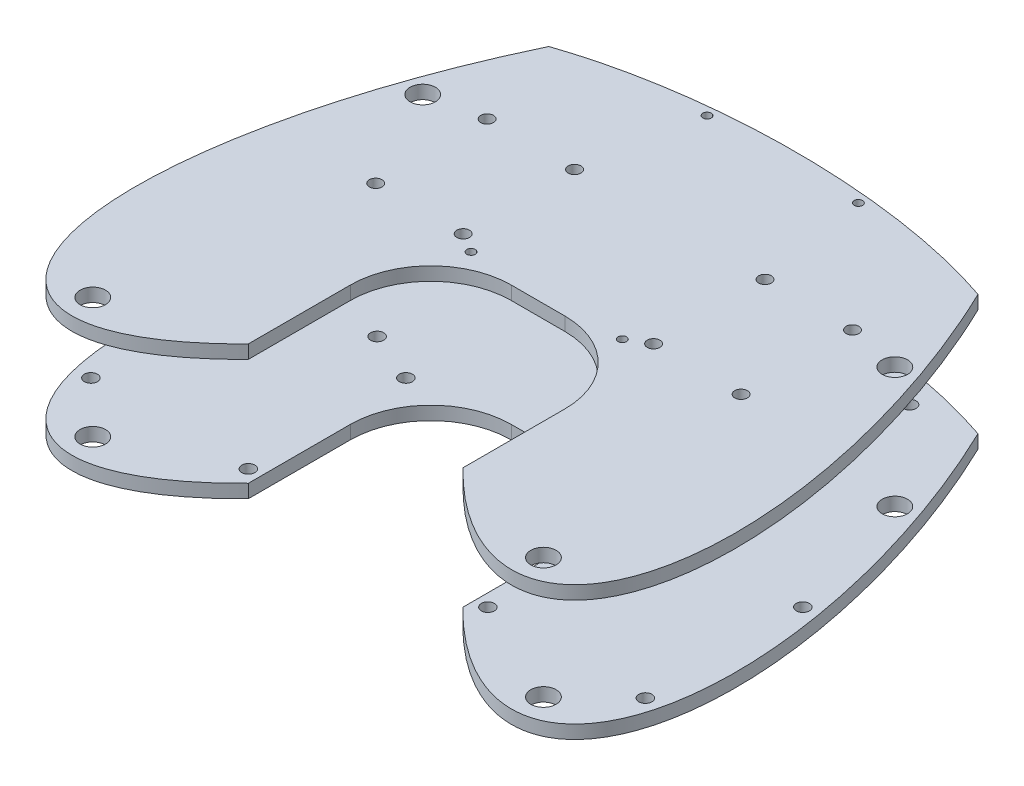
SolidWorks part; units mm, degrees
ref_plane "Front Plane" through (0, 0, 0) normal (0, 0, 1) x (1, 0, 0)
ref_plane "Top Plane" through (0, 0, 0) normal (0, 1, 0) x (1, 0, 0)
ref_plane "Right Plane" through (0, 0, 0) normal (1, 0, 0) x (0, 0, -1)
sketch "Sketch1" plane through (0, 0, 0) normal (0, 1, 0) x (1, 0, 0)
  line L1 (-50.8, -26.67) -> (50.8, -26.67) construction
  line L2 (-50.8, -26.67) -> (-50.8, 26.67) construction
  line L3 (-50.8, 26.67) -> (50.8, 26.67) construction
  line L4 (50.8, -26.67) -> (50.8, 26.67) construction
  line L5 (-50.8, -26.67) -> (50.8, 26.67) construction
  line L6 (-50.8, 26.67) -> (50.8, -26.67) construction
  line L7 (-68.58, -26.67) -> (-25.4, -26.67) construction
  line L8 (-68.58, -26.67) -> (-68.58, -69.85) construction
  line L9 (-68.58, -69.85) -> (-25.4, -69.85) construction
  line L10 (-25.4, -26.67) -> (-25.4, -69.85) construction
  line L11 (-68.58, -26.67) -> (-25.4, -69.85) construction
  line L12 (-68.58, -69.85) -> (-25.4, -26.67) construction
  line L13 (0, -55) -> (0, 55) construction
  line L14 (68.58, -69.85) -> (25.4, -69.85) construction
  line L15 (25.4, -26.67) -> (25.4, -69.85) construction
  line L16 (68.58, -26.67) -> (25.4, -26.67) construction
  line L17 (68.58, -26.67) -> (68.58, -69.85) construction
  line L18 (-55, 0) -> (55, 0) construction
  line L19 (-25.4, -69.85) -> (-25.4, -45.72)
  line L20 (-6.35, -26.67) -> (6.35, -26.67)
  line L21 (25.4, -45.72) -> (25.4, -69.85)
  line L22 (-55.88, 1.9042) -> (-50.8, 1.9042) construction
  line L23 (-55.88, 1.9042) -> (-60.96, 1.9042) construction
  circle A0 centre (-65.63, -66.9) radius 1.55
  circle A1 centre (-65.63, -29.62) radius 1.55
  circle A2 centre (-28.35, -66.9) radius 1.55
  circle A3 centre (-28.35, -29.62) radius 1.55
  circle A4 centre (36.75, 24.52) radius 1.55
  circle A5 centre (35.65, -24.52) radius 1.55
  circle A6 centre (-46.25, 24.52) radius 1.55
  circle A7 centre (-40.25, -24.52) radius 1.55
  circle A8 centre (28.35, -66.9) radius 1.55
  circle A9 centre (65.63, -66.9) radius 1.55
  circle A10 centre (65.63, -29.62) radius 1.55
  circle A11 centre (28.35, -29.62) radius 1.55
  arc A12 (6.35, -26.67) -> (25.4, -45.72) centre (6.35, -45.72) cw
  arc A13 (-25.4, -45.72) -> (-6.35, -26.67) centre (-6.35, -45.72) cw
  circle A14 centre (-55.88, 1.9042) radius 3
  circle A15 centre (-53.34, -78.74) radius 3
  circle A16 centre (53.34, -78.74) radius 3
  circle A17 centre (55.88, 1.9042) radius 3
  ellipse E0 centre (0, 0) end of major axis (-80.8223, 0) minor radius 34.29 construction
  ellipse E1 centre (-23.7067, 0) end of major axis (-57.6304, -83.9384) minor radius 35.5769 construction
  ellipse E2 centre (-23.7067, 0) end of major axis (-57.6304, -83.9384) minor radius 35.5769 (-50.8, 26.67) -> (-25.4, -69.85) ccw
  ellipse E3 centre (23.7067, 0) end of major axis (57.6304, -83.9384) minor radius 35.5769 (50.8, 26.67) -> (25.4, -69.85) cw
  ellipse E4 centre (0, 0) end of major axis (-80.8223, 0) minor radius 34.29 (50.8, 26.67) -> (-50.8, 26.67) ccw
  point P0 (0, 0)
  point P6 (-46.99, -48.26)
  dimension "D5" = 3.1
  dimension "D6" = 2.95
  dimension "D15" = 19.05
  dimension "D16" = 6
  dimension "D18" = 6
  dimension "D1" = 101.6
  dimension "D2" = 53.34
  dimension "D3" = 43.18
  dimension "D4" = 50.8
  dimension "D7" = 2.95
  dimension "D8" = 14.05
  dimension "D9" = 2.15
  dimension "D10" = 15.15
  dimension "D11" = 2.15
  dimension "D12" = 4.55
  dimension "D13" = 10.55
  dimension "D14" = 7.62
  dimension "D17" = 5.08
  dimension "D19" = 8.89
  dimension "D20" = 15.24
extrude "Boss-Extrude1" add sketch "Sketch1" along normal blind 3.175 contours E3 E4 E2 L19 A13 L20 A12 L21 A10 A3 A0 A1 A2 A4 A5 A6 A7 A8 A9 A11
sketch "Sketch2" plane through (0, 3.175, 0) normal (0, 1, 0) x (1, 0, 0)
  line L0 (25.4, -45.72) -> (25.4, -69.85) construction
  line L1 (-25.4, -69.85) -> (-25.4, -45.72) construction
  line L2 (-6.35, -26.67) -> (6.35, -26.67) construction
  line L3 (25.4, -45.72) -> (25.4, -69.85)
  line L4 (-25.4, -69.85) -> (-25.4, -45.72)
  line L5 (-6.35, -26.67) -> (6.35, -26.67)
  line L6 (0, -1.7463) -> (0, 1.7463) construction
  line L7 (-19.939, 33.274) -> (19.939, 33.274) construction
  line L8 (-19.939, 33.274) -> (-19.939, -26.67) construction
  line L9 (-19.939, -26.67) -> (19.939, -26.67) construction
  line L10 (19.939, 33.274) -> (19.939, -26.67) construction
  line L11 (-19.939, 33.274) -> (19.939, -26.67) construction
  line L12 (-19.939, -26.67) -> (19.939, 33.274) construction
  line L13 (45.847, -26.67) -> (19.939, -26.67) construction
  line L14 (-45.847, 7.112) -> (-19.939, 7.112) construction
  line L15 (-45.847, 7.112) -> (-45.847, -26.67) construction
  line L16 (-45.847, -26.67) -> (-19.939, -26.67) construction
  line L17 (-19.939, 7.112) -> (-19.939, -26.67) construction
  line L18 (-45.847, 7.112) -> (-19.939, -26.67) construction
  line L19 (-45.847, -26.67) -> (-19.939, 7.112) construction
  line L20 (19.939, 7.112) -> (19.939, -26.67) construction
  line L21 (45.847, 7.112) -> (19.939, 7.112) construction
  line L22 (45.847, 7.112) -> (45.847, -26.67) construction
  arc A0 (25.4, -45.72) -> (6.35, -26.67) centre (6.35, -45.72) ccw construction
  arc A1 (-6.35, -26.67) -> (-25.4, -45.72) centre (-6.35, -45.72) ccw construction
  arc A2 (25.4, -45.72) -> (6.35, -26.67) centre (6.35, -45.72) ccw
  arc A3 (-6.35, -26.67) -> (-25.4, -45.72) centre (-6.35, -45.72) ccw
  circle A4 centre (-17.907, 31.242) radius 1
  circle A5 centre (-17.907, -24.638) radius 1
  circle A6 centre (17.907, 31.242) radius 1
  circle A7 centre (17.907, -24.638) radius 1
  circle A8 centre (-43.247, 4.512) radius 1.5
  circle A9 centre (-22.539, 4.512) radius 1.5
  circle A10 centre (-43.247, -21.87) radius 1.5
  circle A11 centre (-22.539, -21.87) radius 1.5
  circle A12 centre (43.247, -21.87) radius 1.5
  circle A13 centre (22.539, -21.87) radius 1.5
  circle A14 centre (22.539, 4.512) radius 1.5
  circle A15 centre (43.247, 4.512) radius 1.5
  circle A16 centre (-53.34, -78.74) radius 3 construction
  circle A17 centre (53.34, -78.74) radius 3 construction
  circle A18 centre (55.88, 1.9042) radius 3 construction
  circle A19 centre (-55.88, 1.9042) radius 3 construction
  circle A20 centre (-53.34, -78.74) radius 3
  circle A21 centre (53.34, -78.74) radius 3
  circle A22 centre (55.88, 1.9042) radius 3
  circle A23 centre (-55.88, 1.9042) radius 3
  ellipse E0 centre (23.7067, 0) end of major axis (57.6304, -83.9384) minor radius 35.5769 (25.4, -69.85) -> (50.8, 26.67) ccw construction
  ellipse E1 centre (-23.7067, 0) end of major axis (-57.6304, -83.9384) minor radius 35.5769 (-50.8, 26.67) -> (-25.4, -69.85) ccw construction
  ellipse E2 centre (0, 0) end of major axis (-80.8223, 0) minor radius 34.29 (50.8, 26.67) -> (-50.8, 26.67) ccw construction
  ellipse E3 centre (23.7067, 0) end of major axis (57.6304, -83.9384) minor radius 35.5769 (25.4, -69.85) -> (50.8, 26.67) ccw
  ellipse E4 centre (-23.7067, 0) end of major axis (-57.6304, -83.9384) minor radius 35.5769 (-50.8, 26.67) -> (-25.4, -69.85) ccw
  ellipse E5 centre (0, 0) end of major axis (-80.8223, 0) minor radius 34.29 (50.8, 26.67) -> (-50.8, 26.67) ccw
  point P37 (0, 3.302)
  point P52 (-32.893, -9.779)
  point P63 (0, 0)
  point P66 (0, 0)
  point P67 (0, 0)
  dimension "D3" = 2
  dimension "D11" = 3
  dimension "D1" = 59.944
  dimension "D2" = 39.878
  dimension "D4" = 2.032
  dimension "D5" = 2.032
  dimension "D6" = 2.032
  dimension "D7" = 2.032
  dimension "D8" = 33.782
  dimension "D9" = 25.908
  dimension "D10" = 2.6
  dimension "D12" = 2.6
  dimension "D13" = 2.6
  dimension "D14" = 2.6
  dimension "D15" = 4.8
extrude "Boss-Extrude2" add sketch "Sketch2" along normal blind 3.175 from offset 25.4 separate body
